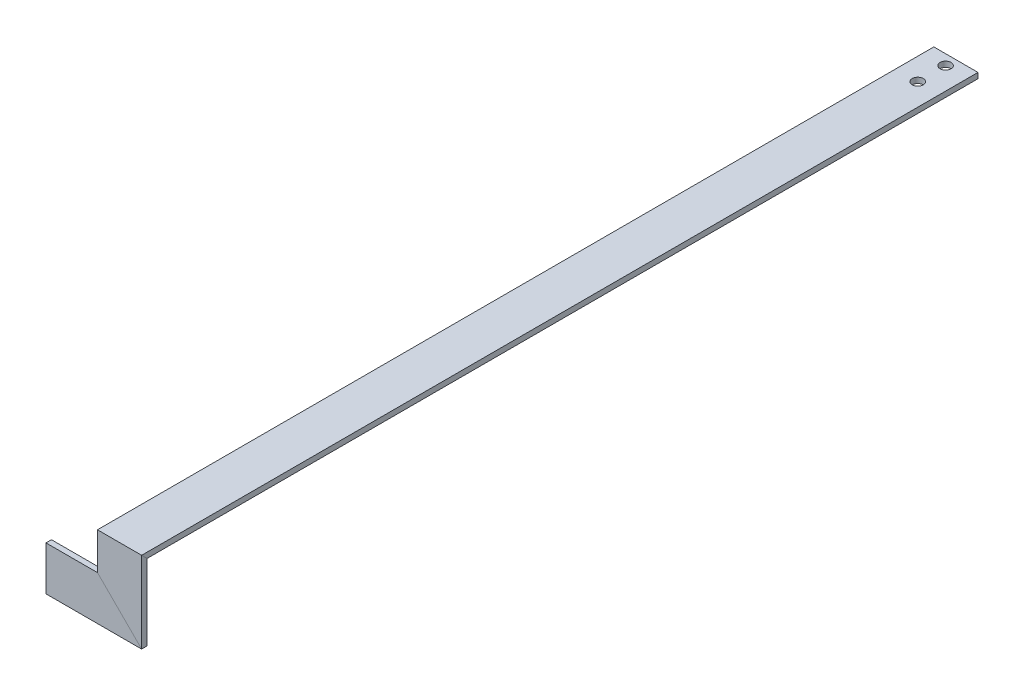
SolidWorks part; units mm, degrees
ref_plane "Alzado" through (0, 0, 0) normal (0, 0, 1) x (1, 0, 0)
ref_plane "Planta" through (0, 0, 0) normal (0, 1, 0) x (1, 0, 0)
ref_plane "Vista lateral" through (0, 0, 0) normal (1, 0, 0) x (0, 0, -1)
sketch "Croquis1" plane through (0, 0, 0) normal (0, 0, 1) x (1, 0, 0)
  line L1 (-25.4, 3.155) -> (25.4, 3.155)
  line L2 (-25.4, 3.155) -> (-25.4, -3.155)
  line L3 (-25.4, -3.155) -> (25.4, -3.155)
  line L4 (25.4, 3.155) -> (25.4, -3.155)
  line L5 (-25.4, 3.155) -> (25.4, -3.155) construction
  line L6 (-25.4, -3.155) -> (25.4, 3.155) construction
  point P0 (0, 0)
  dimension "D1" = 50.8
  dimension "D2" = 6.31
sketch3d "Croquis3D1"
  line L0 (0, 0, 0) -> (0, 0, 958.84)
  line L1 (0, 0, 958.84) -> (0, -64.9, 958.84)
  line L2 (0, -64.9, 958.84) -> (-84.6, -64.9, 958.84)
  dimension "D1" = 958.84
  dimension "D2" = 64.9
  dimension "D3" = 84.6
sweep "Barrer1" add profiles "Croquis1" path "Croquis3D1"
sketch "Croquis2" plane through (0, 3.155, 0) normal (0, 1, 0) x (1, 0, 0)
  circle A0 centre (0, -43.8922) radius 6.35
  circle A1 centre (0, -11.8922) radius 6.35
extrude "Cortar-Extruir1" cut sketch "Croquis2" against normal blind 6.31
